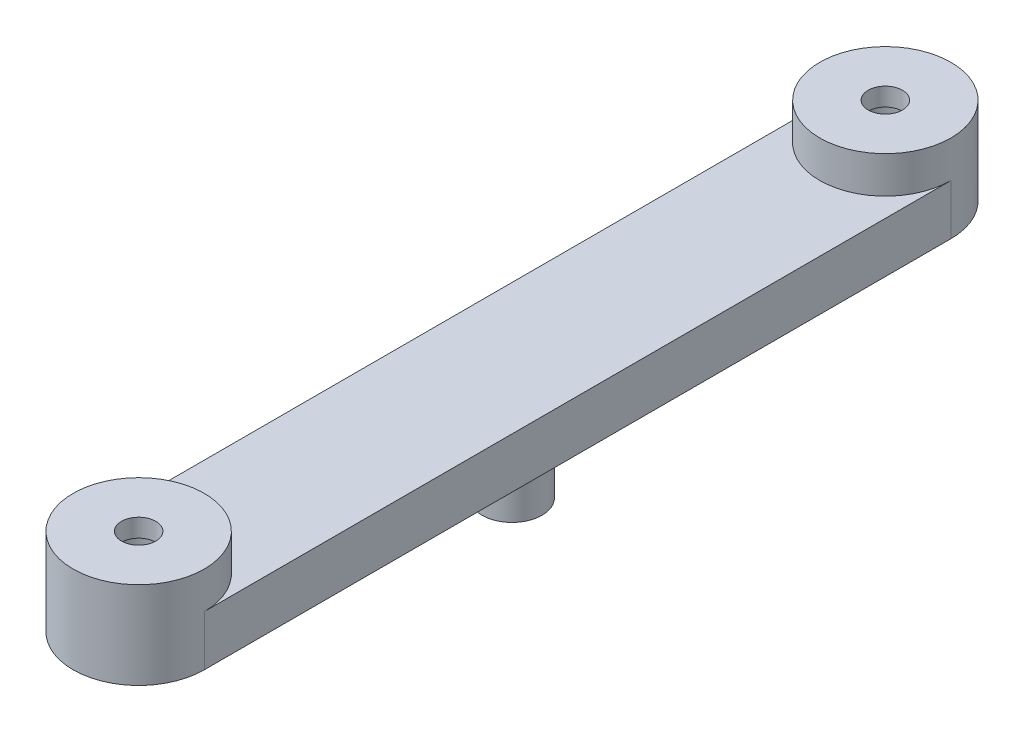
SolidWorks part; units mm, degrees
material "Aleación 6061"
ref_plane "Alzado" through (0, 0, 0) normal (0, 0, 1) x (1, 0, 0)
ref_plane "Planta" through (0, 0, 0) normal (0, 1, 0) x (1, 0, 0)
ref_plane "Vista lateral" through (0, 0, 0) normal (1, 0, 0) x (0, 0, -1)
sketch "Sk_Barra" plane through (0, 0, 0) normal (0, 1, 0) x (1, 0, 0)
  line L1 (-6.5, -207) -> (6.5, -207)
  line L2 (-6.5, -207) -> (-6.5, -133)
  line L3 (-6.5, -133) -> (6.5, -133)
  line L4 (6.5, -207) -> (6.5, -133)
  line L5 (-6.5, -207) -> (6.5, -133) construction
  line L6 (-6.5, -133) -> (6.5, -207) construction
  point P0 (0, -170)
  dimension "D1" = 13
  dimension "D2" = 74
  dimension "D3" = 170
extrude "Barra" add sketch "Sk_Barra" along normal blind 5 from offset 44.75
sketch "Sk_Extremos" plane through (0, 0, 0) normal (0, 1, 0) x (1, 0, 0)
  circle A0 centre (0, -133) radius 6.5
  circle A1 centre (0, -207) radius 6.5
  dimension "D1" = 13
  dimension "D3" = 13
  dimension "D2" = 133
  dimension "D4" = 207
extrude "Extremos" add sketch "Sk_Extremos" along normal blind 8.65 from offset 44.75
sketch "Sk_Perno_696" plane through (0, 0, 0) normal (0, 1, 0) x (1, 0, 0)
  circle A0 centre (0, -170) radius 2.975
  dimension "D1" = 5.95
  dimension "D2" = 170
extrude "Perno_696" add sketch "Sk_Perno_696" along normal blind 7 from offset 51.75
sketch "Sk_Pasantes_M3" plane through (0, 0, 0) normal (0, 1, 0) x (1, 0, 0)
  circle A0 centre (0, -133) radius 1.7
  circle A1 centre (0, -207) radius 1.7
  dimension "D1" = 3.4
  dimension "D3" = 3.4
  dimension "D2" = 133
  dimension "D4" = 207
extrude "Pasantes_M3" cut sketch "Sk_Pasantes_M3" along normal blind 8.65 from offset 44.75
sketch "Sk_Cajas_M3" plane through (0, 0, 0) normal (0, 1, 0) x (1, 0, 0)
  circle A0 centre (0, -133) radius 3
  circle A1 centre (0, -207) radius 3
  dimension "D1" = 6
  dimension "D3" = 6
  dimension "D2" = 133
  dimension "D4" = 207
extrude "Cajas_M3" cut sketch "Sk_Cajas_M3" along normal blind 6.85 from offset 44.75
